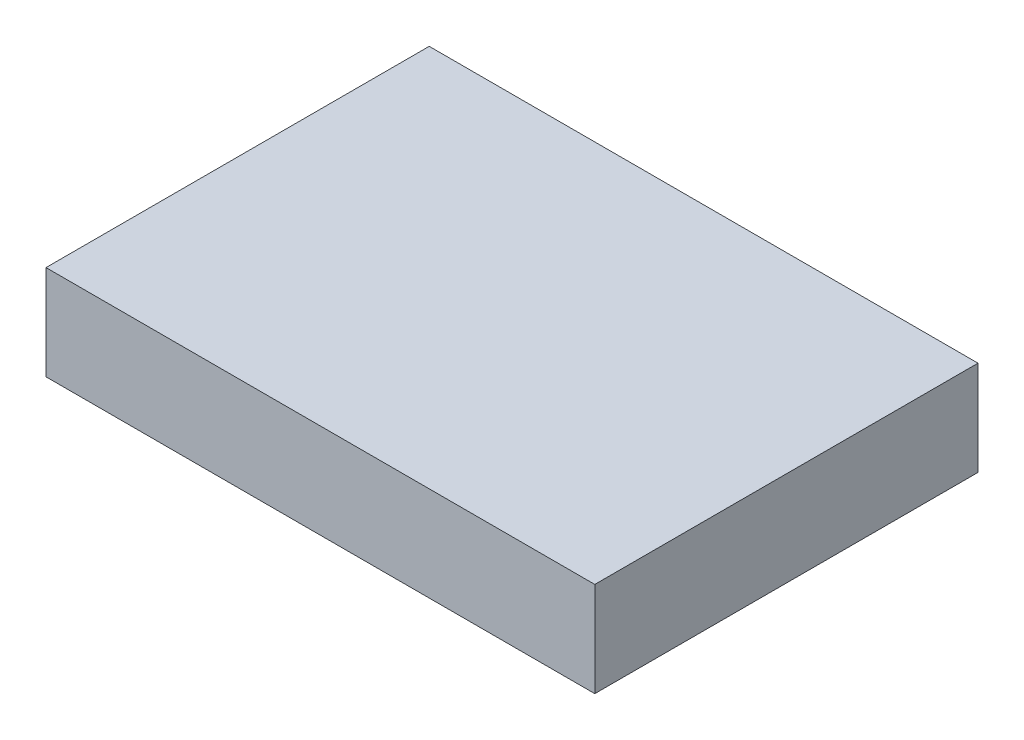
SolidWorks part; units mm, degrees
ref_plane "Front Plane" through (0, 0, 0) normal (0, 0, 1) x (1, 0, 0)
ref_plane "Top Plane" through (0, 0, 0) normal (0, 1, 0) x (1, 0, 0)
ref_plane "Right Plane" through (0, 0, 0) normal (1, 0, 0) x (0, 0, -1)
sketch "Sketch1" plane through (0, 0, 0) normal (0, 1, 0) x (1, 0, 0)
  line L1 (-50, 32.5) -> (50, 32.5) construction
  line L2 (-50, 32.5) -> (-50, -32.5) construction
  line L3 (-50, -32.5) -> (50, -32.5) construction
  line L4 (50, 32.5) -> (50, -32.5) construction
  line L5 (-50, 32.5) -> (50, -32.5) construction
  line L6 (-50, -32.5) -> (50, 32.5) construction
  line L10 (-58, 40.5) -> (58, 40.5)
  line L11 (58, 40.5) -> (58, -40.5)
  line L12 (-58, -40.5) -> (58, -40.5)
  line L13 (-58, 40.5) -> (-58, -40.5)
  point P0 (0, 0)
  dimension "D1" = 100
  dimension "D2" = 65
  dimension "D3" = 8
extrude "Boss-Extrude1" add sketch "Sketch1" along normal blind 20
